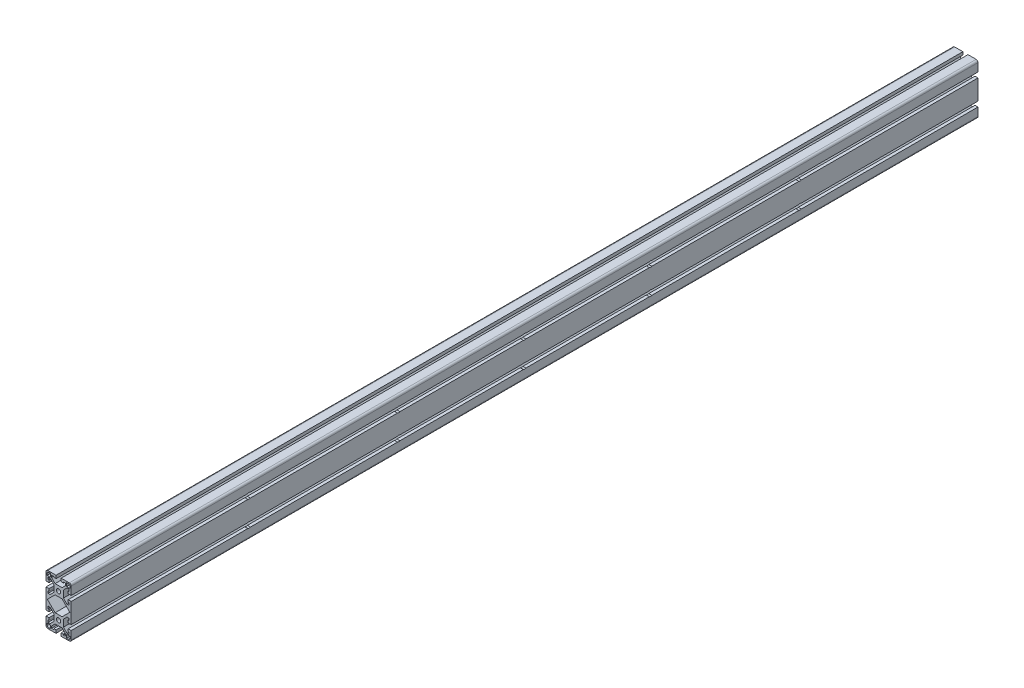
SolidWorks part; units mm, degrees
material "6063-T6"
ref_plane "Front Plane" through (0, 0, 0) normal (0, 0, 1) x (1, 0, 0)
ref_plane "Top Plane" through (0, 0, 0) normal (0, 1, 0) x (1, 0, 0)
ref_plane "Right Plane" through (0, 0, 0) normal (1, 0, 0) x (0, 0, -1)
sketch "Sketch1" plane through (0, 0, 0) normal (0, 1, 0) x (1, 0, 0)
  line L0 (0, 720) -> (0, -720)
  dimension "D1" = 1440
other "40 series TS40-80LM-650037(2)"
ref_plane "Plane4" through (0, 0, -720) normal (0, 0, 1) x (1, 0, 0)
sketch "Sketch2" plane through (0, 0, -720) normal (0, 0, 1) x (1, 0, 0)
  line L2 (0, -27.681) -> (-5.5257, -27.681)
  line L3 (-5.5257, -27.681) -> (-11.176, -33.3313)
  line L4 (-7.6835, -36.6218) -> (-11.176, -36.6218)
  line L5 (-20, -37) -> (-20, -24.0488)
  line L6 (-4.0488, -40) -> (-17, -40)
  line L7 (-7.681, -20) -> (-7.681, -25.5257)
  line L8 (-7.681, -25.5257) -> (-13.3313, -31.176)
  line L9 (-16.6218, -31.176) -> (-16.6218, -27.6835)
  line L10 (-7.681, -14.4743) -> (-13.3313, -8.824)
  line L11 (-13.3313, -8.824) -> (-16.6218, -8.824)
  line L12 (-20, -24.0488) -> (-15.2248, -24.0488)
  line L13 (-20, 15.9512) -> (-20, -15.9512)
  line L14 (-5.5257, 12.319) -> (-17.8447, 0)
  line L15 (-5.5257, -12.319) -> (-17.8447, 0)
  line L16 (-7.681, -20) -> (-7.681, -14.4743)
  line L17 (-5.5257, -12.319) -> (0, -12.319)
  line L18 (7.681, -20) -> (7.681, -14.4743)
  line L19 (5.5257, -12.319) -> (17.8447, 0)
  line L20 (20, 15.9512) -> (15.2248, 15.9512)
  line L21 (4.0488, -35.2248) -> (7.6835, -35.2248)
  line L22 (7.681, 14.4743) -> (13.3313, 8.824)
  line L23 (7.6835, -36.6218) -> (7.6835, -35.2248)
  line L24 (4.0488, -35.2248) -> (4.0488, -40)
  line L25 (7.6835, -36.6218) -> (11.176, -36.6218)
  line L26 (11.176, -33.3313) -> (11.176, -36.6218)
  line L27 (7.681, -20) -> (7.681, -25.5257)
  line L28 (4.0488, -40) -> (17, -40)
  line L29 (20, -37) -> (20, -24.0488)
  line L30 (5.5257, -27.681) -> (11.176, -33.3313)
  line L31 (7.681, -25.5257) -> (13.3313, -31.176)
  line L32 (0, -12.319) -> (5.5257, -12.319)
  line L33 (0, -27.681) -> (5.5257, -27.681)
  line L35 (13.3313, 8.824) -> (16.6218, 8.824)
  line L36 (0, 12.319) -> (5.5257, 12.319)
  line L37 (-5.5257, 12.319) -> (0, 12.319)
  line L38 (16.6218, 8.824) -> (16.6218, 12.3165)
  line L39 (15.2248, 15.9512) -> (15.2248, 12.3165)
  line L40 (16.6218, 12.3165) -> (15.2248, 12.3165)
  line L41 (20, 24.0488) -> (15.2248, 24.0488)
  line L42 (0, 27.681) -> (5.5257, 27.681)
  line L43 (-4.0488, 40) -> (-17, 40)
  line L44 (-20, 37) -> (-20, 24.0488)
  line L45 (4.0488, 35.2248) -> (4.0488, 40)
  line L46 (16.6218, 31.176) -> (16.6218, 27.6835)
  line L47 (7.681, 20) -> (7.681, 25.5257)
  line L48 (13.3313, 31.176) -> (16.6218, 31.176)
  line L49 (15.2248, 24.0488) -> (15.2248, 27.6835)
  line L50 (7.681, 20) -> (7.681, 14.4743)
  line L51 (-7.681, 25.5257) -> (-7.681, 14.4743)
  line L52 (16.6218, 27.6835) -> (15.2248, 27.6835)
  line L53 (12.8372, 38.222) -> (12.8372, 32.8372)
  line L54 (20, 37) -> (20, 24.0488)
  line L55 (4.0488, 40) -> (17, 40)
  line L56 (12.8372, 38.222) -> (15.428, 38.222)
  line L57 (18.222, 35.428) -> (18.222, 32.8372)
  line L58 (12.8372, 32.8372) -> (18.222, 32.8372)
  line L59 (0, 27.681) -> (-5.5257, 27.681)
  line L60 (-4.0488, -35.2248) -> (-4.0488, -40)
  line L61 (-16.6218, -8.824) -> (-16.6218, -12.3165)
  line L62 (7.681, -14.4743) -> (13.3313, -8.824)
  line L63 (12.8372, -32.8372) -> (18.222, -32.8372)
  line L64 (20, 15.9512) -> (20, -15.9512)
  line L65 (7.681, 25.5257) -> (13.3313, 31.176)
  line L66 (5.5257, 27.681) -> (11.176, 33.3313)
  line L67 (5.5257, 12.319) -> (17.8447, 0)
  line L68 (-13.3313, -31.176) -> (-16.6218, -31.176)
  line L69 (-11.176, -33.3313) -> (-11.176, -36.6218)
  line L70 (-15.2248, -15.9512) -> (-15.2248, -12.3165)
  line L71 (-12.8372, -38.222) -> (-12.8372, -32.8372)
  line L72 (-12.8372, -38.222) -> (-15.428, -38.222)
  line L73 (-15.2248, -24.0488) -> (-15.2248, -27.6835)
  line L74 (-16.6218, -27.6835) -> (-15.2248, -27.6835)
  line L75 (-18.222, -35.428) -> (-18.222, -32.8372)
  line L76 (-12.8372, -32.8372) -> (-18.222, -32.8372)
  line L77 (-7.6835, -36.6218) -> (-7.6835, -35.2248)
  line L78 (-4.0488, -35.2248) -> (-7.6835, -35.2248)
  line L79 (-20, -15.9512) -> (-15.2248, -15.9512)
  line L80 (-16.6218, -12.3165) -> (-15.2248, -12.3165)
  line L81 (18.222, -35.428) -> (18.222, -32.8372)
  line L82 (12.8372, -38.222) -> (15.428, -38.222)
  line L83 (12.8372, -38.222) -> (12.8372, -32.8372)
  line L84 (16.6218, -12.3165) -> (15.2248, -12.3165)
  line L85 (20, -15.9512) -> (15.2248, -15.9512)
  line L86 (16.6218, -27.6835) -> (15.2248, -27.6835)
  line L87 (15.2248, -24.0488) -> (15.2248, -27.6835)
  line L88 (15.2248, -15.9512) -> (15.2248, -12.3165)
  line L89 (13.3313, -31.176) -> (16.6218, -31.176)
  line L90 (16.6218, -8.824) -> (16.6218, -12.3165)
  line L91 (20, -24.0488) -> (15.2248, -24.0488)
  line L92 (13.3313, -8.824) -> (16.6218, -8.824)
  line L93 (16.6218, -31.176) -> (16.6218, -27.6835)
  line L94 (11.176, 33.3313) -> (11.176, 36.6218)
  line L95 (7.6835, 36.6218) -> (11.176, 36.6218)
  line L96 (7.6835, 36.6218) -> (7.6835, 35.2248)
  line L97 (4.0488, 35.2248) -> (7.6835, 35.2248)
  line L98 (-4.0488, 35.2248) -> (-4.0488, 40)
  line L99 (-4.0488, 35.2248) -> (-7.6835, 35.2248)
  line L100 (-7.6835, 36.6218) -> (-7.6835, 35.2248)
  line L101 (-7.6835, 36.6218) -> (-11.176, 36.6218)
  line L102 (-11.176, 33.3313) -> (-11.176, 36.6218)
  line L103 (-5.5257, 27.681) -> (-11.176, 33.3313)
  line L104 (-18.222, 35.428) -> (-18.222, 32.8372)
  line L105 (-12.8372, 32.8372) -> (-18.222, 32.8372)
  line L106 (-7.681, 25.5257) -> (-13.3313, 31.176)
  line L107 (-13.3313, 31.176) -> (-16.6218, 31.176)
  line L108 (-16.6218, 31.176) -> (-16.6218, 27.6835)
  line L109 (-7.681, 14.4743) -> (-13.3313, 8.824)
  line L110 (-16.6218, 12.3165) -> (-15.2248, 12.3165)
  line L111 (-20, 15.9512) -> (-15.2248, 15.9512)
  line L112 (-15.2248, 15.9512) -> (-15.2248, 12.3165)
  line L113 (-16.6218, 8.824) -> (-16.6218, 12.3165)
  line L114 (-13.3313, 8.824) -> (-16.6218, 8.824)
  line L115 (-16.6218, 27.6835) -> (-15.2248, 27.6835)
  line L116 (-15.2248, 24.0488) -> (-15.2248, 27.6835)
  line L117 (-20, 24.0488) -> (-15.2248, 24.0488)
  line L118 (-12.8372, 38.222) -> (-15.428, 38.222)
  line L119 (-12.8372, 38.222) -> (-12.8372, 32.8372)
  arc A0 (-20, -37) -> (-17, -40) centre (-17, -37) ccw
  arc A1 (-20, 37) -> (-17, 40) centre (-17, 37) cw
  arc A2 (20, 37) -> (17, 40) centre (17, 37) ccw
  arc A3 (-15.428, -38.222) -> (-18.222, -35.428) centre (-15.428, -35.428) cw
  arc A4 (15.428, -38.222) -> (18.222, -35.428) centre (15.428, -35.428) ccw
  arc A5 (15.428, 38.222) -> (18.222, 35.428) centre (15.428, 35.428) cw
  arc A6 (-15.428, 38.222) -> (-18.222, 35.428) centre (-15.428, 35.428) ccw
  arc A7 (20, -37) -> (17, -40) centre (17, -37) cw
  circle A8 centre (0, -20) radius 3.35
  circle A9 centre (0, 20) radius 3.35
  point P1 (-20, 20)
  point P3 (-20, 40)
  point P34 (-20, 0)
  point P51 (20, 0)
  point P76 (0, 40)
  point P77 (20, 40)
  point P143 (20, 20)
  point P144 (20, -20)
  point P145 (-20, -20)
  point P146 (-20, -40)
  point P147 (0, -40)
  point P148 (20, -40)
  point P149 (0, 0)
  dimension "D1" = 6.7
hole_wizard "M8x1.25 Tapped Hole1" positions "Sketch3" profile "Sketch4" tap size "M8x1.25" standard "ANSI Metric"
sketch "Sketch3" plane through (0, 0, 720) normal (0, 0, 1) x (1, 0, 0)
  point P0 (0, 20)
  point P3 (0, -20)
sketch "Sketch4" plane through (0, 20, 720) normal (1, 0, 0) x (0, -1, 0)
  line L0 (0, 0) -> (0, 32.0429)
  line L1 (0, 32.0429) -> (3.4, 30)
  line L2 (3.4, 30) -> (3.4, 0)
  line L5 (3.4, 0) -> (0, 0)
  line L10 (0, 32.0429) -> (-3.4, 30) construction
  line L11 (0, -6.35) -> (0, 107.95) construction
  dimension "Tap Drill Dia." = 6.8
  dimension "Tap Drill Depth" = 30
  dimension "Drill Angle" = 118
cosmetic thread "Hole Thread1" parameters "D1"=25, "D2"=8
cosmetic thread "Hole Thread2" parameters "D1"=25, "D2"=8
hole_wizard "M8x1.25 Tapped Hole2" positions "Sketch5" profile "Sketch6" tap size "M8x1.25" standard "ANSI Metric"
sketch "Sketch5" plane through (0, 0, -720) normal (0, 0, -1) x (-1, 0, 0)
  point P0 (0, 20)
  point P3 (0, -20)
sketch "Sketch6" plane through (0, 20, -720) normal (1, 0, 0) x (0, 1, 0)
  line L0 (0, 0) -> (0, 32.0429)
  line L1 (0, 32.0429) -> (3.4, 30)
  line L2 (3.4, 30) -> (3.4, 0)
  line L5 (3.4, 0) -> (0, 0)
  line L10 (0, 32.0429) -> (-3.4, 30) construction
  line L11 (0, -6.35) -> (0, 107.95) construction
  dimension "Tap Drill Dia." = 6.8
  dimension "Tap Drill Depth" = 30
  dimension "Drill Angle" = 118
cosmetic thread "Hole Thread3" parameters "D1"=25, "D2"=8
cosmetic thread "Hole Thread4" parameters "D1"=25, "D2"=8
hole_wizard "M8 Clearance Hole1" positions "Sketch7" profile "Sketch8" hole size "M8" standard "ANSI Metric" end condition through all
sketch "Sketch7" plane through (-20, 0, 0) normal (-1, 0, 0) x (0, 0, 1)
  line L0 (-200, 0) -> (200, 0)
  line L3 (200, 20) -> (200, -20)
  line L6 (-200, -20) -> (-200, 20)
  point P6 (200, 20)
  point P7 (200, -20)
  point P11 (-200, -20)
  point P12 (-200, 20)
  dimension "D1" = 40
  dimension "D2" = 400
sketch "Sketch8" plane through (-20, 20, -200) normal (0, 1, 0) x (0, 0, 1)
  line L0 (0, 0) -> (0, 40)
  line L1 (0, 40) -> (4.5, 40)
  line L2 (4.5, 40) -> (4.5, 0)
  line L5 (4.5, 0) -> (0, 0)
  line L11 (0, -6.35) -> (0, 107.95) construction
  dimension "Thru Hole Dia." = 9
  dimension "Thru Hole Depth" = 40
hole_wizard "M8 Clearance Hole2" positions "Sketch9" profile "Sketch10" hole size "M8" standard "ANSI Metric" end condition through all
sketch "Sketch9" plane through (-20, 0, 0) normal (-1, 0, 0) x (0, 0, 1)
  line L1 (-437.5, -20) -> (437.5, -20)
  line L2 (-437.5, -20) -> (-437.5, 20)
  line L3 (-437.5, 20) -> (437.5, 20)
  line L4 (437.5, -20) -> (437.5, 20)
  line L5 (0, -20) -> (0, 20)
  point P1 (-437.5, -20)
  point P2 (437.5, 20)
  point P87 (-437.5, 20)
  point P88 (437.5, -20)
  point P90 (0, -20)
  point P91 (0, 20)
  dimension "D1" = 875
  dimension "D2" = 40
sketch "Sketch10" plane through (-20, -20, -437.5) normal (0, 1, 0) x (0, 0, 1)
  line L0 (0, 0) -> (0, 40)
  line L1 (0, 40) -> (4.5, 40)
  line L2 (4.5, 40) -> (4.5, 0)
  line L5 (4.5, 0) -> (0, 0)
  line L11 (0, -6.35) -> (0, 107.95) construction
  dimension "Thru Hole Dia." = 9
  dimension "Thru Hole Depth" = 40
